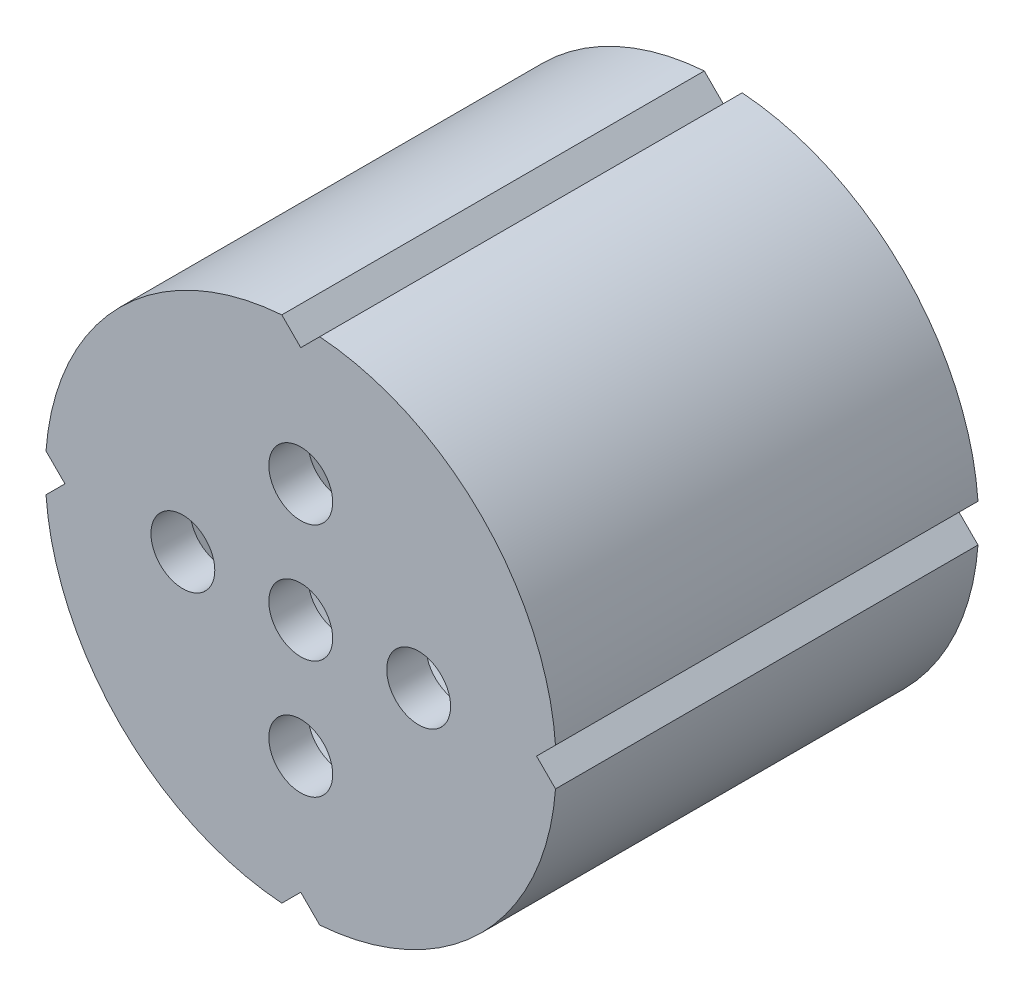
SolidWorks part; units mm, degrees
ref_plane "Alzado" through (0, 0, 0) normal (0, 0, 1) x (1, 0, 0)
ref_plane "Planta" through (0, 0, 0) normal (0, 1, 0) x (1, 0, 0)
ref_plane "Vista lateral" through (0, 0, 0) normal (1, 0, 0) x (0, 0, -1)
sketch "Croquis1" plane through (0, 0, 0) normal (0, 0, 1) x (1, 0, 0)
  line L0 (0, -11.5) -> (0, -12) construction
  line L1 (11.5, 0) -> (12, 0) construction
  line L2 (0, 12) -> (1, 12) construction
  line L3 (-11.5, 0) -> (-12, 0) construction
  line L4 (0, 11.5) -> (0, 12) construction
  line L5 (0, 12) -> (-1, 12) construction
  line L8 (0.9642, 12.9642) -> (0, 12)
  line L12 (-0.9642, 12.9642) -> (0, 12)
  line L13 (-12, 0) -> (-12, -1) construction
  line L14 (-12, 0) -> (-12, 1) construction
  line L17 (-12.9642, 0.9642) -> (-12, 0)
  line L18 (-12, 0) -> (-12.9642, -0.9642)
  line L20 (12, 0) -> (12, 1) construction
  line L21 (12, 0) -> (12, -1) construction
  line L24 (12.9642, -0.9642) -> (12, 0)
  line L25 (12, 1) -> (12.9615, 1) construction
  line L26 (12.9642, 0.9642) -> (12, 0)
  line L28 (0, -12) -> (1, -12) construction
  line L29 (0, -12) -> (-1, -12) construction
  line L32 (0.9642, -12.9642) -> (0, -12)
  line L34 (0, -12) -> (-0.9642, -12.9642)
  circle A0 centre (0, 0) radius 11.5
  arc A1 (0.9642, -12.9642) -> (12.9642, -0.9642) centre (0, 0) ccw
  arc A2 (12.9642, 0.9642) -> (0.9642, 12.9642) centre (0, 0) ccw
  arc A3 (-0.9642, 12.9642) -> (-12.9642, 0.9642) centre (0, 0) ccw
  arc A4 (-12.9642, -0.9642) -> (-0.9642, -12.9642) centre (0, 0) ccw
  dimension "D1" = 23
  dimension "D2" = 13
  dimension "D3" = 0.9642
  dimension "D4" = 1
extrude "Saliente-Extruir1" add sketch "Croquis1" against normal blind 19.5
sketch "Croquis2" plane through (0, 0, 0) normal (0, 0, 1) x (1, 0, 0)
  line L0 (-12.9642, -0.9642) -> (-12, 0)
  line L1 (-12, 0) -> (-12.9642, 0.9642)
  line L2 (0, -12) -> (0.9642, -12.9642)
  line L3 (-0.9642, -12.9642) -> (0, -12)
  line L4 (12.9642, -0.9642) -> (12, 0)
  line L5 (12, 0) -> (12.9642, 0.9642)
  line L6 (-0.9642, 12.9642) -> (0, 12)
  line L7 (0, 12) -> (0.9642, 12.9642)
  line L8 (0, 0) -> (6, 0) construction
  line L9 (0, 0) -> (-6, 0) construction
  line L10 (0, 0) -> (0, -6) construction
  line L11 (0, 0) -> (0, 6) construction
  arc A0 (-12.9642, 0.9642) -> (-0.9642, 12.9642) centre (0, 0) cw
  arc A1 (0.9642, 12.9642) -> (12.9642, 0.9642) centre (0, 0) cw
  arc A2 (12.9642, -0.9642) -> (0.9642, -12.9642) centre (0, 0) cw
  arc A3 (-0.9642, -12.9642) -> (-12.9642, -0.9642) centre (0, 0) cw
  circle A4 centre (0, 0) radius 1.625
  circle A5 centre (6, 0) radius 1.625
  circle A6 centre (-6, 0) radius 1.625
  circle A7 centre (0, 6) radius 1.625
  circle A8 centre (0, -6) radius 1.625
  dimension "D1" = 3.25
  dimension "D2" = 6.9642
extrude "Saliente-Extruir2" add sketch "Croquis2" along normal blind 2
